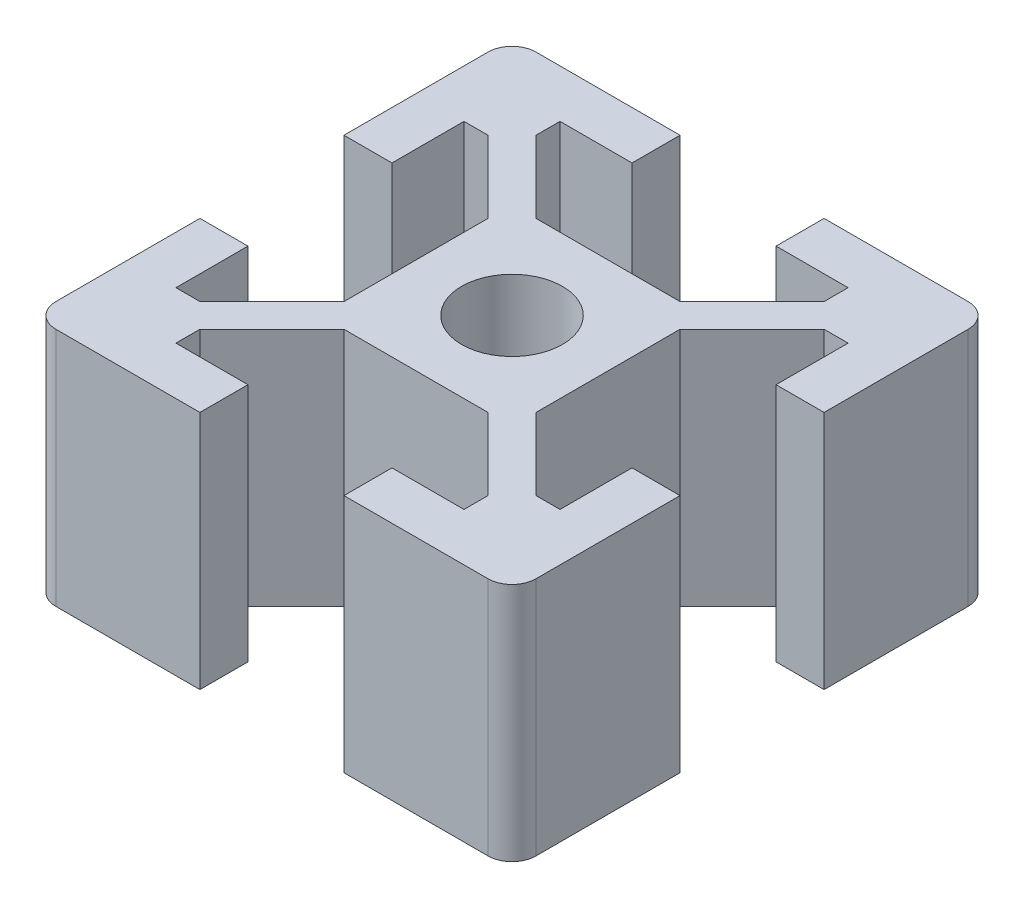
SolidWorks part; units mm, degrees
ref_plane "Front Plane" through (0, 0, 0) normal (0, 0, 1) x (1, 0, 0)
ref_plane "Top Plane" through (0, 0, 0) normal (0, 1, 0) x (1, 0, 0)
ref_plane "Right Plane" through (0, 0, 0) normal (1, 0, 0) x (0, 0, -1)
sketch "Sketch1" plane through (0, 0, 0) normal (0, 1, 0) x (1, 0, 0)
  line L5 (-3, 10) -> (-10, 10)
  line L6 (-4, 3) -> (-7, 6)
  line L7 (-4, -4) -> (4, -4)
  line L8 (-4, -4) -> (-4, 4)
  line L9 (-4, 4) -> (4, 4)
  line L10 (4, -4) -> (4, 4)
  line L11 (-8, 6) -> (-7, 6)
  line L12 (-8, 6) -> (-8, 3)
  line L16 (-3, 8) -> (-3, 10)
  line L21 (-8, 3) -> (-10, 3)
  line L22 (-6, 8) -> (-6, 7)
  line L23 (-10, 3) -> (-10, 10)
  line L24 (-3, 4) -> (-6, 7)
  line L25 (3, 10) -> (10, 10)
  line L26 (6, 8) -> (3, 8)
  line L27 (-6, 8) -> (-3, 8)
  line L28 (3, 8) -> (3, 10)
  line L29 (-10, 10) -> (-4, 4)
  line L30 (6, 8) -> (6, 7)
  line L31 (3, 4) -> (6, 7)
  line L32 (4, 3) -> (7, 6)
  line L33 (8, 6) -> (7, 6)
  line L34 (8, 6) -> (8, 3)
  line L35 (8, 3) -> (10, 3)
  line L36 (10, 3) -> (10, 10)
  line L37 (10, -3) -> (10, -10)
  line L38 (8, -6) -> (8, -3)
  line L39 (8, -3) -> (10, -3)
  line L40 (8, -6) -> (7, -6)
  line L41 (4, -3) -> (7, -6)
  line L42 (3, -4) -> (6, -7)
  line L43 (6, -8) -> (6, -7)
  line L44 (6, -8) -> (3, -8)
  line L45 (3, -8) -> (3, -10)
  line L46 (3, -10) -> (10, -10)
  line L47 (-3, -10) -> (-10, -10)
  line L48 (-6, -8) -> (-3, -8)
  line L49 (-3, -8) -> (-3, -10)
  line L50 (-6, -8) -> (-6, -7)
  line L51 (-3, -4) -> (-6, -7)
  line L52 (-4, -3) -> (-7, -6)
  line L53 (-8, -6) -> (-7, -6)
  line L54 (-8, -6) -> (-8, -3)
  line L55 (-8, -3) -> (-10, -3)
  line L56 (-10, -3) -> (-10, -10)
  circle A0 centre (0, 0) radius 2.1
  point P0 (0, 0)
  point P55 (0, 0)
  dimension "D3" = 3
  dimension "D1" = 4.2
  dimension "D2" = 4
  dimension "D4" = 4
  dimension "D5" = 6
  dimension "D7" = 8
  dimension "D8" = 10
  dimension "D6" = 4
extrude "Boss-Extrude1" add sketch "Sketch1" along normal blind 10 contours L29 L23 L21 L12 L11 L6 L8 | L5 L29 L9 L24 L22 L27 L16 | L35 L36 L25 L28 L26 L30 L31 L9 L10 L32 L33 L34 | L7 L10 L9 L8 A0 | L45 L46 L37 L39 L38 L40 L41 L10 L7 L42 L43 L44 | L55 L56 L47 L49 L48 L50 L51 L7 L8 L52 L53 L54
fillet "Fillet1" radius 1 4 edges at (-10, 5, 10) (-10, 5, -10) (10, 5, -10) (10, 5, 10)
